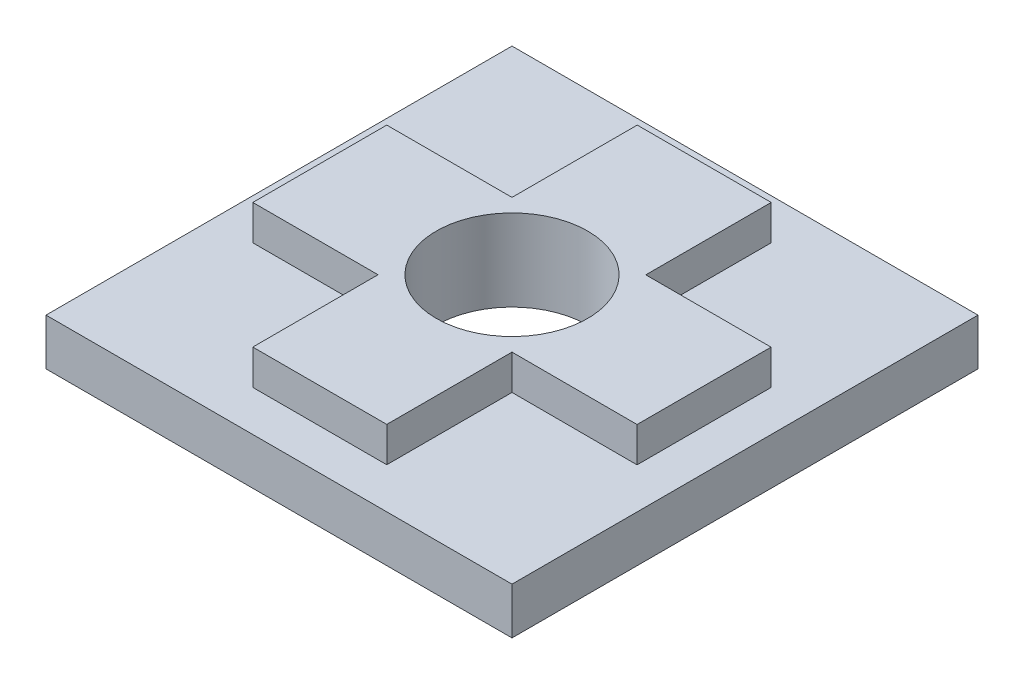
SolidWorks part; units mm, degrees
ref_plane "Front Plane" through (0, 0, 0) normal (0, 0, 1) x (1, 0, 0)
ref_plane "Top Plane" through (0, 0, 0) normal (0, 1, 0) x (1, 0, 0)
ref_plane "Right Plane" through (0, 0, 0) normal (1, 0, 0) x (0, 0, -1)
sketch "Sketch1" plane through (0, 0, 0) normal (0, 1, 0) x (1, 0, 0)
  line L1 (-10, 10) -> (10, 10)
  line L2 (-10, 10) -> (-10, -10)
  line L3 (-10, -10) -> (10, -10)
  line L4 (10, 10) -> (10, -10)
  line L5 (-10, 10) -> (10, -10) construction
  line L6 (-10, -10) -> (10, 10) construction
  point P0 (0, 0)
extrude "Boss-Extrude1" add sketch "Sketch1" along normal blind 2
sketch "Sketch3" plane through (0, 2, 0) normal (0, 1, 0) x (1, 0, 0)
  line L0 (-2.875, 8.25) -> (2.875, 8.25)
  line L1 (0, -55) -> (0, 55) construction
  line L2 (8.25, -2.8825) -> (8.25, 2.8675)
  line L3 (-2.875, 8.25) -> (-2.875, 2.875)
  line L4 (-2.875, -8.25) -> (2.875, -8.25)
  line L5 (-8.25, -2.875) -> (-8.25, 2.875)
  line L6 (-2.875, 2.875) -> (-8.25, 2.875)
  line L7 (-55, 0) -> (55, 0) construction
  line L8 (-8.25, -2.875) -> (-2.875, -2.875)
  line L9 (-2.875, -2.875) -> (-2.875, -8.25)
  line L10 (2.875, -8.25) -> (2.875, -2.875)
  line L11 (2.875, -2.875) -> (8.25, -2.8825)
  line L12 (8.25, 2.8675) -> (2.875, 2.8675)
  line L13 (2.875, 2.8675) -> (2.875, 8.25)
  point P2 (0, 8.25)
  point P8 (8.25, -0.0075)
  point P11 (0, -8.25)
  point P14 (-8.25, 0)
extrude "Boss-Extrude3" add sketch "Sketch3" along normal blind 1.5
hole_wizard "Tap Drill for M2.2 Helicoil1" positions "3DSketch1" profile "Sketch5" hole size "M2.2x0.45" standard "ANSI Metric" end condition through all
sketch3d "3DSketch1"
  point P0 (0, 3.5, 0)
  point P3 (0, 0, 0)
sketch "Sketch5" plane through (0, 3.5, 0) normal (1, 0, 0) x (0, 0, 1)
  line L0 (0, 0) -> (0, 3.5)
  line L1 (0, 3.5) -> (3.25, 3.5)
  line L2 (3.25, 3.5) -> (3.25, 0)
  line L5 (3.25, 0) -> (0, 0)
  line L11 (0, -6.35) -> (0, 107.95) construction
  dimension "Thru Hole Dia." = 6.5
  dimension "Thru Hole Depth" = 3.5
